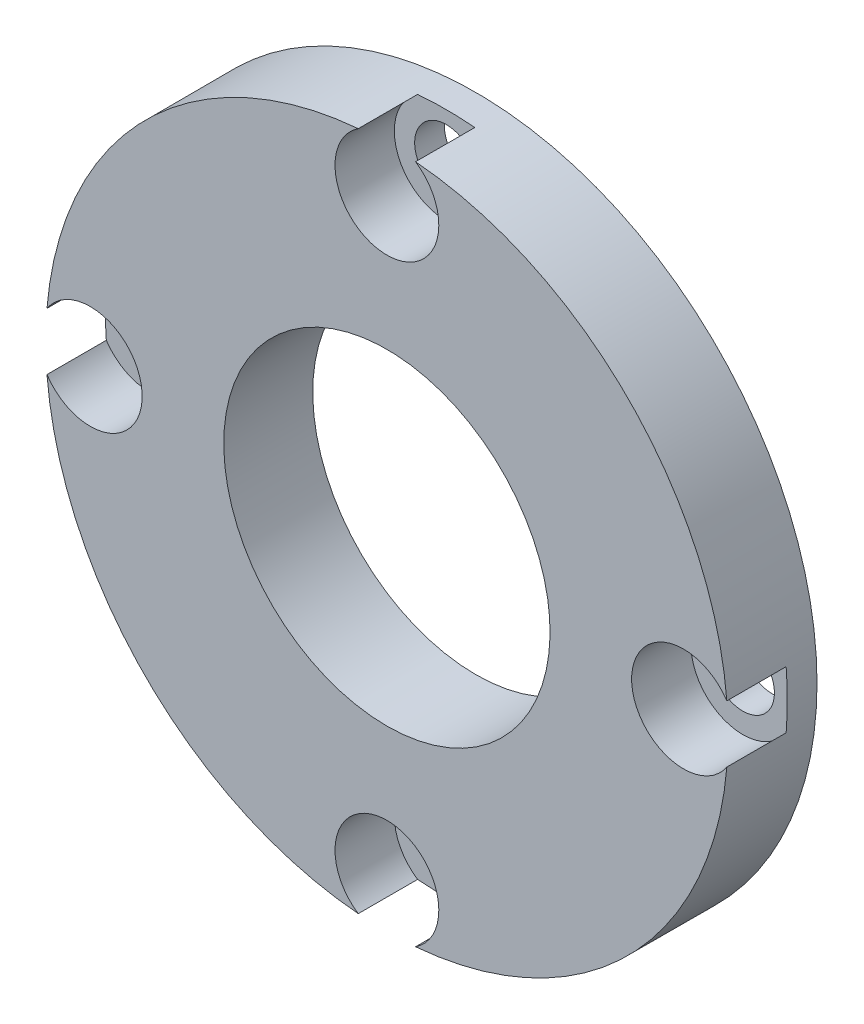
SolidWorks part; units mm, degrees
ref_plane "Front Plane" through (0, 0, 0) normal (0, 0, 1) x (1, 0, 0)
ref_plane "Top Plane" through (0, 0, 0) normal (0, 1, 0) x (1, 0, 0)
ref_plane "Right Plane" through (0, 0, 0) normal (1, 0, 0) x (0, 0, -1)
sketch "Sketch1" plane through (0, 0, 0) normal (0, 0, 1) x (1, 0, 0)
  circle A0 centre (0, 0) radius 36.5125
  circle A2 centre (0, 0) radius 31.75 construction
  point P5 (0, 31.75)
  point P6 (31.75, 0)
  point P7 (-31.75, 0)
  point P8 (0, -31.75)
  dimension "D1" = 73.025
  dimension "D2" = 63.5
extrude "Extrude1" add sketch "Sketch1" along normal blind 9.525
sketch "Sketch2" plane through (0, 0, 9.525) normal (0, 0, 1) x (-1, 0, 0)
  circle A14 centre (0, 0) radius 17.4625
  dimension "D2" = 34.925
extrude "Shaft thru hole" cut sketch "Sketch2" against normal through all
hole_wizard "CBORE for 1/4 Socket Head Cap Screw1" positions "Sketch5" profile "Sketch4" counterbore size "1/4" standard "Ansi Inch" end condition through all
sketch "Sketch5" plane through (0, 0, 9.525) normal (0, 0, 1) x (1, 0, 0)
  circle A0 centre (0, 0) radius 31.75 construction
  point P0 (0, 31.75)
  point P1 (-31.75, 0)
  point P3 (31.75, 0)
  point P5 (0, -31.75)
  dimension "D1" = 63.5
sketch "Sketch4" plane through (0, 31.75, 9.525) normal (1, 0, 0) x (0, -1, 0)
  line L0 (0, 0) -> (0, 9.525)
  line L1 (0, 9.525) -> (3.3782, 9.525)
  line L3 (3.3782, 9.525) -> (3.3782, 6.35)
  line L4 (3.3782, 6.35) -> (5.5562, 6.35)
  line L5 (5.5562, 6.35) -> (5.5563, 0)
  line L7 (5.5563, 0) -> (0, 0)
  line L11 (0, -6.35) -> (0, 107.95) construction
  dimension "Thru Hole Dia." = 6.7564
  dimension "Thru Hole Depth" = 9.525
  dimension "C'Bore Dia." = 11.1125
  dimension "C'Bore Depth" = 6.35
